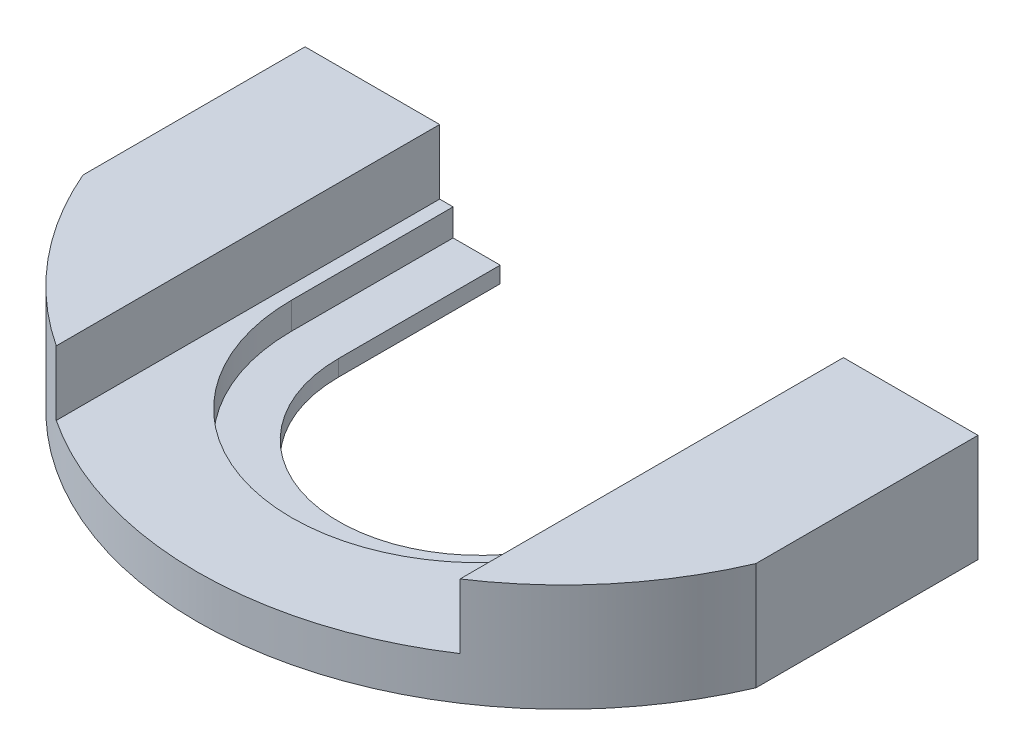
SolidWorks part; units mm, degrees
ref_plane "Plan de face" through (0, 0, 0) normal (0, 0, 1) x (1, 0, 0)
ref_plane "Plan de dessus" through (0, 0, 0) normal (0, 1, 0) x (1, 0, 0)
ref_plane "Plan de droite" through (0, 0, 0) normal (1, 0, 0) x (0, 0, -1)
sketch "Esquisse1" plane through (0, 0, 0) normal (0, 0, 1) x (1, 0, 0)
  line L1 (0, 0) -> (10, 0)
  line L2 (0, 0) -> (0, 8)
  line L3 (0, 8) -> (10, 8)
  line L4 (10, 0) -> (10, 8)
  line L5 (-30, 8) -> (-40, 8)
  line L6 (-30, 8) -> (-30, 0)
  line L7 (-30, 0) -> (-40, 0)
  line L8 (-40, 8) -> (-40, 0)
  line L9 (-30, 0) -> (0, 0)
  line L10 (-30, 0) -> (-30, 1.2)
  line L11 (-30, 1.2) -> (0, 1.2)
  line L12 (0, 0) -> (0, 1.2)
  dimension "D1" = 1.2
  dimension "D2" = 8
  dimension "D3" = 10
  dimension "D4" = 30
extrude "Boss.-Extru.1" add sketch "Esquisse1" along normal blind 33 contours L5 L8 L7 L6 | L1 L4 L3 L2 | L9 L12 L11 L10
sketch "Esquisse2" plane through (0, 0, 0) normal (0, -1, 0) x (1, 0, 0)
  line L0 (-40, 33) -> (-40, 0) construction
  line L1 (10, 0) -> (-40, 0) construction
  line L4 (-25.5, 12) -> (-25.5, 0)
  line L5 (-4.5, 12) -> (-4.5, 0)
  circle A0 centre (-15, 12) radius 10.5
  line M1 (-40, 0) -> (10, 0)
  dimension "D1" = 25
  dimension "D2" = 21
  dimension "D3" = 12
extrude "Enlèv. mat.-Extru.3" cut sketch "Esquisse2" against normal blind 30 contours A0 L5 M1
fillet "Congé1" [suppressed] radius 30
fillet "Congé2" [suppressed] radius 30
sketch "Esquisse3" plane through (0, 1.2, 0) normal (0, 1, 0) x (1, 0, 0)
  line L1 (-29, -12) -> (-29, 0)
  line L2 (-30, 0) -> (-25.5, 0) construction
  line L3 (-1, -12) -> (-1, 0)
  line L4 (-4.5, 0) -> (0, 0) construction
  line L6 (-30, -33) -> (0, -33)
  line L7 (-30, -33) -> (-30, 0)
  line L8 (-30, 0) -> (0, 0)
  line L9 (0, -33) -> (0, 0)
  circle A0 centre (-15, -12) radius 14
  line M1 (0, 0) -> (-4.5, 0)
  line M5 (-25.5, 0) -> (-30, 0)
  line M6 (-30, 0) -> (-30, -33)
  line M7 (-30, -33) -> (0, -33)
  line M8 (0, -33) -> (0, 0)
  dimension "D1" = 28
extrude "Boss.-Extru.2" add sketch "Esquisse3" along normal blind 2 contours A0 L1 L3 M5 M6 M7 M8 M1
sketch "Esquisse4" plane through (0, 0, 0) normal (0, 0, -1) x (-1, 0, 0)
  line L0 (40, 8) -> (40, 0) construction
  line L2 (25.5, 0) -> (40, 0) construction
  line L3 (0, 8) -> (-10, 8) construction
  line L4 (-10, 0) -> (-10, 8) construction
  circle A0 centre (35, 4) radius 1.5
  circle A1 centre (-5, 4) radius 1.5
  point P0 (35, 4)
  dimension "D3" = 3
  dimension "D4" = 4
  dimension "D6" = 3
  dimension "D1" = 5
  dimension "D2" = 4
  dimension "D5" = 5
extrude "Enlèv. mat.-Extru.4" cut sketch "Esquisse4" against normal blind 10
sketch "Esquisse5" plane through (0, 0, 0) normal (0, -1, 0) x (1, 0, 0)
  line L0 (-40, 33) -> (-40, 0) construction
  line L1 (10, 33) -> (10, 0) construction
  line L2 (10, 33) -> (-40, 33) construction
  line L3 (-40, 16.5) -> (-40, 33)
  line L4 (-40, 33) -> (10, 33)
  line L5 (10, 33) -> (10, 16.5)
  arc A0 (-40, 16.5) -> (10, 16.5) centre (-15, 5.8106) cw
  line M4 (10, 0) -> (10, 33)
  line M5 (10, 33) -> (-40, 33)
  line M6 (-40, 33) -> (-40, 0)
extrude "Enlèv. mat.-Extru.5" cut sketch "Esquisse5" against normal through all contours A0 L4 M6 | A0 M5 M4
